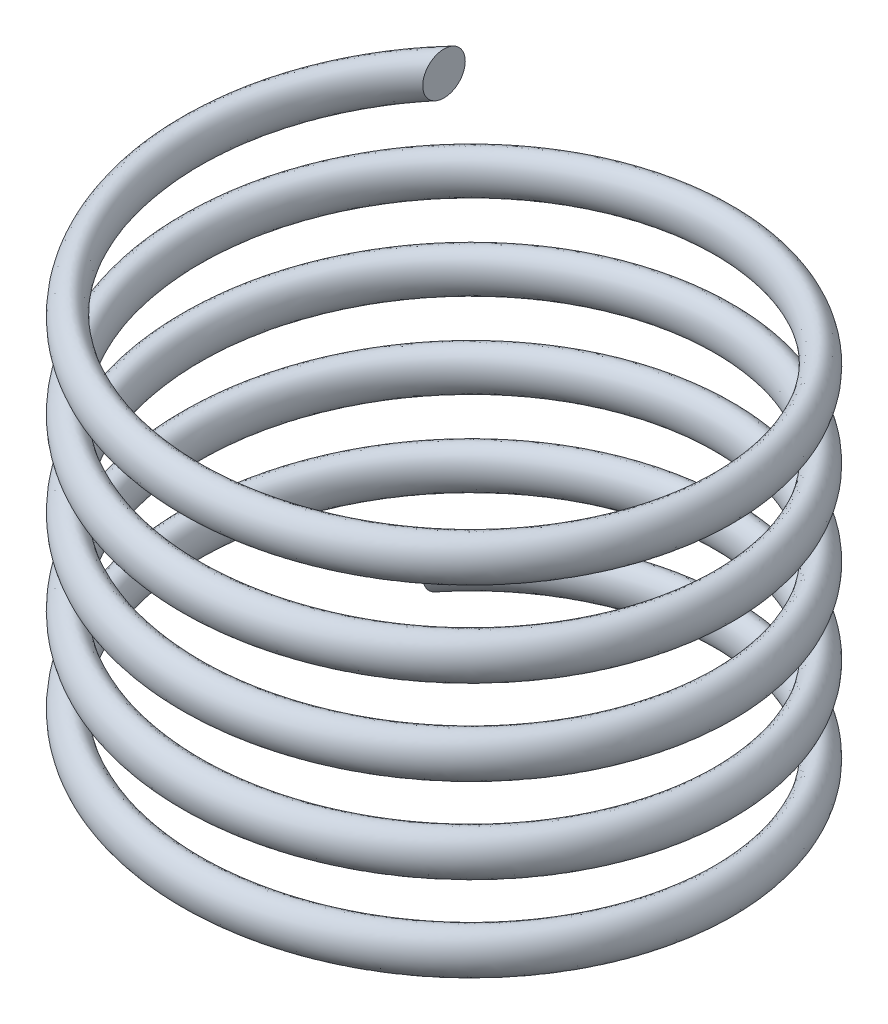
SolidWorks part; units mm, degrees
ref_plane "Front Plane" through (0, 0, 0) normal (0, 0, 1) x (1, 0, 0)
ref_plane "Top Plane" through (0, 0, 0) normal (0, 1, 0) x (1, 0, 0)
ref_plane "Right Plane" through (0, 0, 0) normal (1, 0, 0) x (0, 0, -1)
sketch "Sketch2" plane through (0, 0, 0) normal (0, 1, 0) x (1, 0, 0)
  circle A0 centre (0, 0) radius 25
curve "Helix/Spiral1" pitch 8 height 40 turns 5
ref_plane "Plane1" through (-17.6777, 0, 0) normal (1, 0, 0) x (0, 0, -1)
sketch "Sketch4" plane through (-17.6777, 0, 0) normal (1, 0, 0) x (0, 0, -1)
  circle A0 centre (17.6777, 0) radius 2
  spline S0 degree 3 poles (17.6777, 0) (19.3549, 0.1208) (22.2449, 0.3638) (24.7623, 0.7272) (25.2778, 1.0909) (23.7443, 1.4545) (20.2875, 1.8182) (15.187, 2.1818) (8.8562, 2.5455) (1.8079, 2.9091) (-5.3869, 3.2727) (-12.1452, 3.6364) (-17.9196, 4) (-22.2423, 4.3636) (-24.763, 4.7273) (-25.2776, 5.0909) (-23.7443, 5.4545) (-20.2875, 5.8182) (-15.187, 6.1818) (-8.8562, 6.5455) (-1.8079, 6.9091) (5.3869, 7.2727) (12.1452, 7.6364) (17.9196, 8) (22.2423, 8.3636) (24.763, 8.7273) (25.2776, 9.0909) (23.7443, 9.4545) (20.2875, 9.8182) (15.187, 10.1818) (8.8562, 10.5455) (1.8079, 10.9091) (-5.3869, 11.2727) (-12.1452, 11.6364) (-17.9196, 12) (-22.2423, 12.3636) (-24.763, 12.7273) (-25.2776, 13.0909) (-23.7443, 13.4545) (-20.2875, 13.8182) (-15.187, 14.1818) (-8.8562, 14.5455) (-1.8079, 14.9091) (5.3869, 15.2727) (12.1452, 15.6364) (17.9196, 16) (22.2423, 16.3636) (24.763, 16.7273) (25.2776, 17.0909) (23.7443, 17.4545) (20.2875, 17.8182) (15.187, 18.1818) (8.8562, 18.5455) (1.8079, 18.9091) (-5.3869, 19.2727) (-12.1452, 19.6364) (-17.9196, 20) (-22.2423, 20.3636) (-24.763, 20.7273) (-25.2776, 21.0909) (-23.7443, 21.4545) (-20.2875, 21.8182) (-15.187, 22.1818) (-8.8562, 22.5455) (-1.8079, 22.9091) (5.3869, 23.2727) (12.1452, 23.6364) (17.9196, 24) (22.2423, 24.3636) (24.763, 24.7273) (25.2776, 25.0909) (23.7443, 25.4545) (20.2875, 25.8182) (15.187, 26.1818) (8.8562, 26.5455) (1.8079, 26.9091) (-5.3869, 27.2727) (-12.1452, 27.6364) (-17.9196, 28) (-22.2423, 28.3636) (-24.763, 28.7273) (-25.2776, 29.0909) (-23.7443, 29.4545) (-20.2875, 29.8182) (-15.187, 30.1818) (-8.8562, 30.5455) (-1.8079, 30.9091) (5.3869, 31.2727) (12.1452, 31.6364) (17.9196, 32) (22.2423, 32.3636) (24.763, 32.7273) (25.2776, 33.0909) (23.7443, 33.4545) (20.2875, 33.8182) (15.187, 34.1818) (8.8562, 34.5455) (1.8079, 34.9091) (-5.3869, 35.2727) (-12.1452, 35.6364) (-17.9196, 36) (-22.2423, 36.3636) (-24.763, 36.7273) (-25.2776, 37.0909) (-23.7443, 37.4545) (-20.2875, 37.8182) (-15.187, 38.1818) (-8.8561, 38.5455) (-1.8081, 38.9091) (5.3876, 39.2728) (12.1426, 39.6362) (16.0005, 39.8792) (17.6777, 40) knots 0 0 0 0 0.009091 0.018182 0.027273 0.036364 0.045455 0.054545 0.063636 0.072727 0.081818 0.090909 0.1 0.109091 0.118182 0.127273 0.136364 0.145455 0.154545 0.163636 0.172727 0.181818 0.190909 0.2 0.209091 0.218182 0.227273 0.236364 0.245455 0.254545 0.263636 0.272727 0.281818 0.290909 0.3 0.309091 0.318182 0.327273 0.336364 0.345455 0.354545 0.363636 0.372727 0.381818 0.390909 0.4 0.409091 0.418182 0.427273 0.436364 0.445455 0.454545 0.463636 0.472727 0.481818 0.490909 0.5 0.509091 0.518182 0.527273 0.536364 0.545455 0.554545 0.563636 0.572727 0.581818 0.590909 0.6 0.609091 0.618182 0.627273 0.636364 0.645455 0.654545 0.663636 0.672727 0.681818 0.690909 0.7 0.709091 0.718182 0.727273 0.736364 0.745455 0.754545 0.763636 0.772727 0.781818 0.790909 0.8 0.809091 0.818182 0.827273 0.836364 0.845455 0.854545 0.863636 0.872727 0.881818 0.890909 0.9 0.909091 0.918182 0.927273 0.936364 0.945455 0.954545 0.963636 0.972727 0.981818 0.990909 1 1 1 1 construction
sweep "Sweep1" add profiles "Sketch4" path "Helix/Spiral1"
